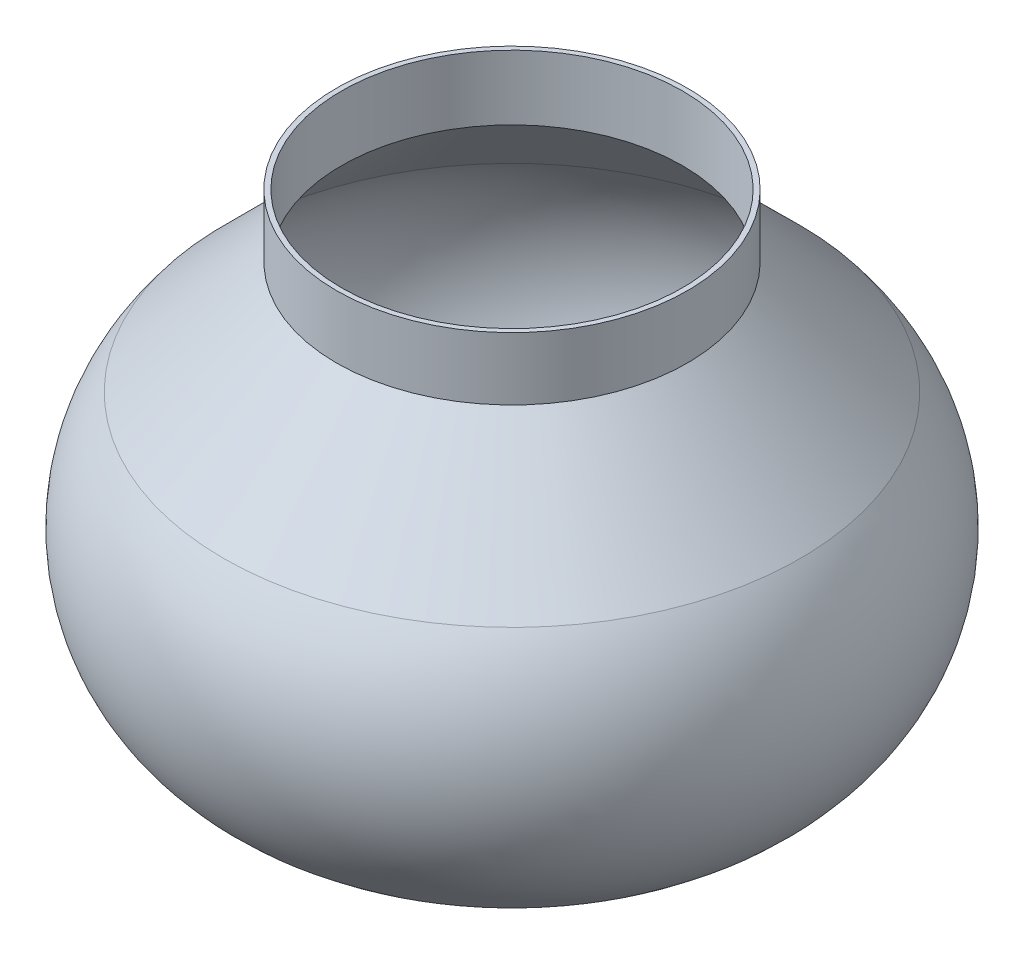
SolidWorks part; units mm, degrees
ref_plane "Front" through (0, 0, 0) normal (0, 0, 1) x (1, 0, 0)
ref_plane "Top" through (0, 0, 0) normal (0, 1, 0) x (1, 0, 0)
ref_plane "Right" through (0, 0, 0) normal (1, 0, 0) x (0, 0, -1)
other "Configuration Table"
sketch "Sketch1" plane through (0, 0, 0) normal (0, 0, 1) x (1, 0, 0)
  line L0 (0, 167.64) -> (0, -48.1974) construction
  line L1 (0, 0) -> (71.12, 0)
  line L2 (-49.6584, 167.64) -> (191.8729, 167.64) construction
  line L3 (116.84, 121.9328) -> (71.1072, 167.64)
  line L4 (71.1072, 167.64) -> (71.1072, 193.04)
  line L5 (69.1072, 166.8112) -> (69.1072, 193.04)
  line L6 (115.3502, 120.5941) -> (69.1072, 166.8112)
  line L7 (0, 2) -> (70.9441, 2)
  line L8 (69.1072, 193.04) -> (71.1072, 193.04)
  line L9 (0, 0) -> (0, 2)
  arc A0 (71.12, 0) -> (116.84, 121.9328) centre (58.0136, 74.4524) ccw
  arc A1 (70.9441, 2) -> (115.3502, 120.5941) centre (58.0136, 74.4524) ccw
  dimension "D2" = 75.5972
  dimension "D1" = 71.12
  dimension "D3" = 116.84
  dimension "D4" = 58.0136
  dimension "D5" = 167.64
  dimension "D6" = 25.4
  dimension "D7" = 64.6578
  dimension "D8" = 2
revolve "Revolve1" add sketch "Sketch1" angle 360 about L0
